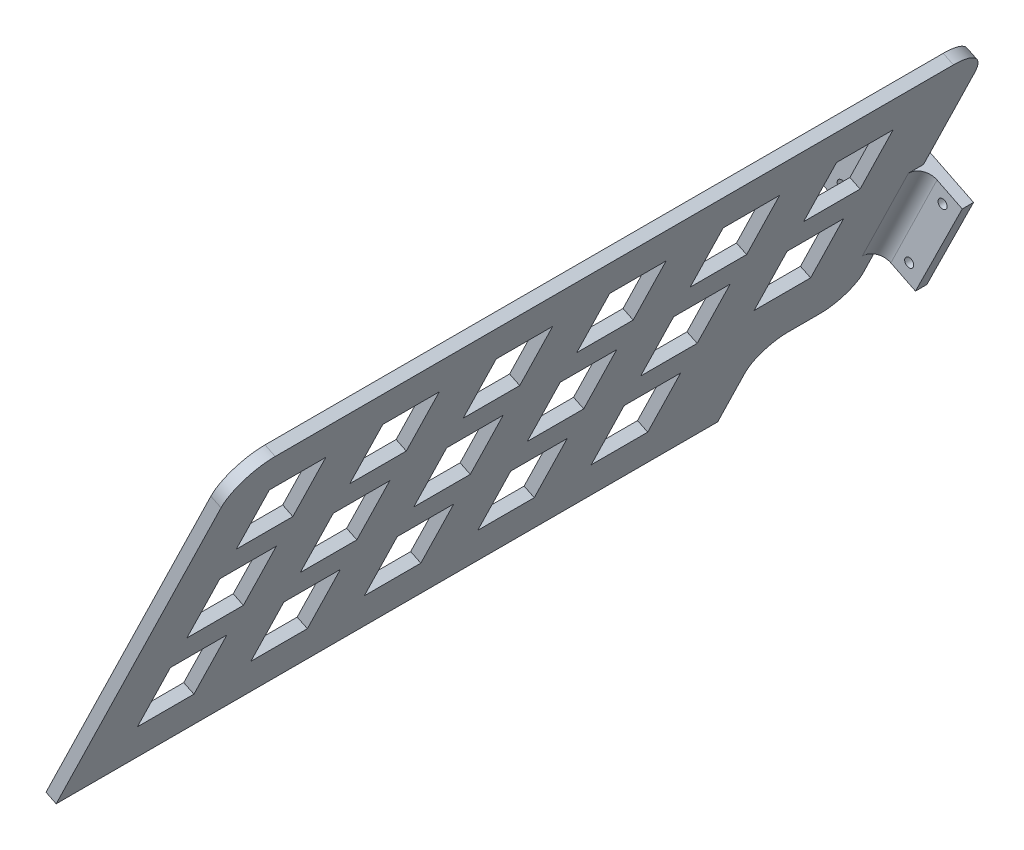
SolidWorks part; units mm, degrees
ref_plane "前视基准面" through (0, 0, 0) normal (0, 0, 1) x (1, 0, 0)
ref_plane "上视基准面" through (0, 0, 0) normal (0, 1, 0) x (1, 0, 0)
ref_plane "右视基准面" through (0, 0, 0) normal (1, 0, 0) x (0, 0, -1)
other "Configuration Table"
sketch "草图1" plane through (0, 0, 0) normal (0, 0, 1) x (1, 0, 0)
  line L0 (-68.5343, 4.2832) -> (-80.9444, -20.8165)
  line L1 (-68.5343, 4.2832) -> (-43.4347, -8.1269)
  line L2 (-80.9444, -20.8165) -> (-55.8447, -33.2265)
  line L3 (-43.4347, -8.1269) -> (-55.8447, -33.2265)
  circle A0 centre (-66.5775, -0.7118) radius 1.2
  circle A1 centre (-75.4419, -18.6401) radius 1.2
  circle A2 centre (-57.5136, -27.5044) radius 1.2
  circle A3 centre (-48.6492, -9.5761) radius 1.2
extrude "凸台-拉伸1" add sketch "草图1" along normal blind 3
sketch "草图2" plane through (0, 0, 3) normal (0, 0, 1) x (1, 0, 0)
  line L0 (-86.6066, -63.7835) -> (-51.6013, 8.1513) construction
  line L1 (-86.6066, -63.7835) -> (-38.4742, 35.1269)
  line L2 (-86.6066, -63.7835) -> (-83.9091, -65.0962)
  line L3 (-38.4742, 35.1269) -> (-35.7767, 33.8142)
  line L4 (-83.9091, -65.0962) -> (-35.7767, 33.8142)
  dimension "D1" = 110
  dimension "D2" = 3
extrude "凸台-拉伸2" add sketch "草图2" along normal blind 200
fillet "圆角1" radius 4 2 edges at (-62.5286, -14.304, 3) (-59.8393, -15.6337, 3)
sketch "草图4" plane through (-44.9286, 21.8634, 0) normal (-0.8992, 0.4376, 0) x (0, 0, 1)
  line L0 (3, -70.7441) -> (27.4347, -70.7441)
  line L1 (3, -54.2227) -> (3, -95.2495) construction
  line L2 (27.4347, -70.7441) -> (27.4347, -95.2495)
  line L3 (203, -95.2495) -> (3, -95.2495) construction
  line L4 (3, -70.7441) -> (3, -95.2495)
  line L5 (3, -95.2495) -> (27.4347, -95.2495)
extrude "切除-拉伸1" cut sketch "草图4" against normal blind 4
fillet "圆角3" radius 8 2 edges at (-74.5351, -42.405, 3) (-74.5351, -42.405, 27.4347)
sketch "草图5" plane through (-42.231, 20.5507, 0) normal (0.8992, -0.4376, 0) x (0, 0, -1)
  line L0 (-67.5646, -20.2495) -> (-67.5646, -0.2495)
  line L1 (-37.4557, -20.2495) -> (-22.4557, -20.2495)
  line L2 (-37.4557, -20.2495) -> (-37.4557, -0.2495)
  line L3 (-37.4557, -0.2495) -> (-22.4557, -0.2495)
  line L4 (-22.4557, -20.2495) -> (-22.4557, -0.2495)
  line L5 (-67.5646, -20.2495) -> (-52.5646, -20.2495)
  line L6 (-52.5646, -20.2495) -> (-52.5646, -0.2495)
  line L7 (-67.5646, -0.2495) -> (-52.5646, -0.2495)
  line L8 (-97.6734, -20.2495) -> (-97.6734, -0.2495)
  line L9 (-97.6734, -20.2495) -> (-82.6734, -20.2495)
  line L10 (-82.6734, -20.2495) -> (-82.6734, -0.2495)
  line L11 (-97.6734, -0.2495) -> (-82.6734, -0.2495)
  line L12 (-127.7823, -20.2495) -> (-127.7823, -0.2495)
  line L13 (-127.7823, -20.2495) -> (-112.7823, -20.2495)
  line L14 (-112.7823, -20.2495) -> (-112.7823, -0.2495)
  line L15 (-127.7823, -0.2495) -> (-112.7823, -0.2495)
  line L16 (-157.8911, -20.2495) -> (-157.8911, -0.2495)
  line L17 (-157.8911, -20.2495) -> (-142.8911, -20.2495)
  line L18 (-142.8911, -20.2495) -> (-142.8911, -0.2495)
  line L19 (-157.8911, -0.2495) -> (-142.8911, -0.2495)
  line L20 (-188, -20.2495) -> (-188, -0.2495)
  line L21 (-188, -20.2495) -> (-173, -20.2495)
  line L22 (-173, -20.2495) -> (-173, -0.2495)
  line L23 (-188, -0.2495) -> (-173, -0.2495)
  line L24 (-67.5646, -50.2495) -> (-67.5646, -30.2495)
  line L25 (-67.5646, -50.2495) -> (-52.5646, -50.2495)
  line L26 (-52.5646, -50.2495) -> (-52.5646, -30.2495)
  line L27 (-67.5646, -30.2495) -> (-52.5646, -30.2495)
  line L28 (-97.6734, -50.2495) -> (-97.6734, -30.2495)
  line L29 (-97.6734, -50.2495) -> (-82.6734, -50.2495)
  line L30 (-82.6734, -50.2495) -> (-82.6734, -30.2495)
  line L31 (-97.6734, -30.2495) -> (-82.6734, -30.2495)
  line L32 (-127.7823, -50.2495) -> (-127.7823, -30.2495)
  line L33 (-127.7823, -50.2495) -> (-112.7823, -50.2495)
  line L34 (-112.7823, -50.2495) -> (-112.7823, -30.2495)
  line L35 (-127.7823, -30.2495) -> (-112.7823, -30.2495)
  line L36 (-157.8911, -50.2495) -> (-157.8911, -30.2495)
  line L37 (-157.8911, -50.2495) -> (-142.8911, -50.2495)
  line L38 (-142.8911, -50.2495) -> (-142.8911, -30.2495)
  line L39 (-157.8911, -30.2495) -> (-142.8911, -30.2495)
  line L40 (-188, -50.2495) -> (-188, -30.2495)
  line L41 (-188, -50.2495) -> (-173, -50.2495)
  line L42 (-173, -50.2495) -> (-173, -30.2495)
  line L43 (-188, -30.2495) -> (-173, -30.2495)
  line L44 (-67.5646, -80.2495) -> (-67.5646, -60.2495)
  line L45 (-67.5646, -80.2495) -> (-52.5646, -80.2495)
  line L46 (-52.5646, -80.2495) -> (-52.5646, -60.2495)
  line L47 (-67.5646, -60.2495) -> (-52.5646, -60.2495)
  line L48 (-97.6734, -80.2495) -> (-97.6734, -60.2495)
  line L49 (-97.6734, -80.2495) -> (-82.6734, -80.2495)
  line L50 (-82.6734, -80.2495) -> (-82.6734, -60.2495)
  line L51 (-97.6734, -60.2495) -> (-82.6734, -60.2495)
  line L52 (-127.7823, -80.2495) -> (-127.7823, -60.2495)
  line L53 (-127.7823, -80.2495) -> (-112.7823, -80.2495)
  line L54 (-112.7823, -80.2495) -> (-112.7823, -60.2495)
  line L55 (-127.7823, -60.2495) -> (-112.7823, -60.2495)
  line L56 (-157.8911, -80.2495) -> (-157.8911, -60.2495)
  line L57 (-157.8911, -80.2495) -> (-142.8911, -80.2495)
  line L58 (-142.8911, -80.2495) -> (-142.8911, -60.2495)
  line L59 (-157.8911, -60.2495) -> (-142.8911, -60.2495)
  line L60 (-188, -80.2495) -> (-188, -60.2495)
  line L61 (-188, -80.2495) -> (-173, -80.2495)
  line L62 (-173, -80.2495) -> (-173, -60.2495)
  line L63 (-188, -60.2495) -> (-173, -60.2495)
  line L64 (-37.4557, -50.2495) -> (-37.4557, -30.2495)
  line L65 (-37.4557, -50.2495) -> (-22.4557, -50.2495)
  line L66 (-22.4557, -50.2495) -> (-22.4557, -30.2495)
  line L67 (-37.4557, -30.2495) -> (-22.4557, -30.2495)
  line L72 (-22.4557, -80.2495) -> (-22.4557, -60.2495) [skipped]
  line L73 (-37.4557, -80.2495) -> (-37.4557, -60.2495) [skipped]
  line L74 (-37.4557, -60.2495) -> (-22.4557, -60.2495) [skipped]
  line L75 (-37.4557, -80.2495) -> (-22.4557, -80.2495) [skipped]
  line L76 (-203, 14.7505) -> (-3, 14.7505) construction
  line L78 (-203, -95.2495) -> (-203, 14.7505) construction
  dimension "D1" = 6
  dimension "D3" = 15
  dimension "D4" = 15
  dimension "D2" = 3
extrude "切除-拉伸2" cut sketch "草图5" against normal blind 10
fillet "圆角4" radius 10 1 edges at (-37.1255, 34.4705, 203)
fillet "圆角5" radius 10 1 edges at (-37.1255, 34.4705, 3)
